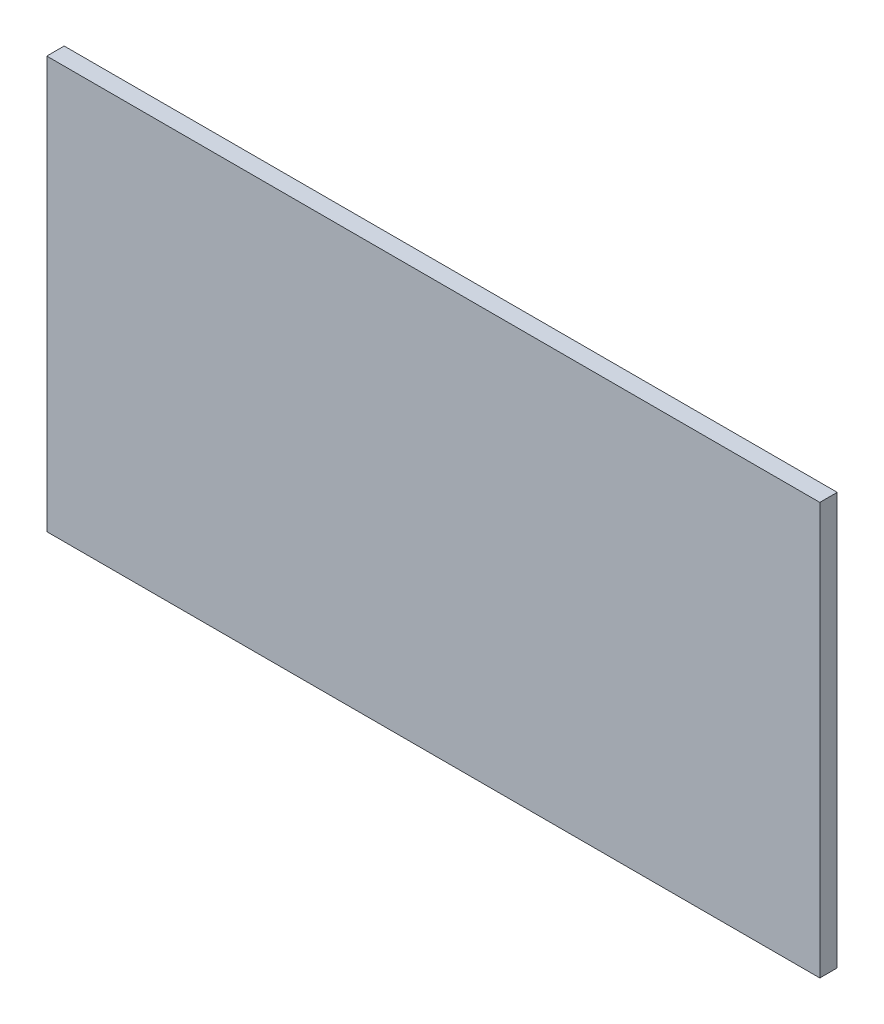
SolidWorks part; units mm, degrees
ref_plane "Alzado" through (0, 0, 0) normal (0, 0, 1) x (1, 0, 0)
ref_plane "Planta" through (0, 0, 0) normal (0, 1, 0) x (1, 0, 0)
ref_plane "Vista lateral" through (0, 0, 0) normal (1, 0, 0) x (0, 0, -1)
sketch "Croquis1" plane through (0, 0, 0) normal (0, 0, 1) x (1, 0, 0)
  line L1 (-57.8963, 16.3831) -> (-13.5012, 16.3831)
  line L2 (-57.8963, 16.3831) -> (-57.8963, -7.2712)
  line L3 (-57.8963, -7.2712) -> (-13.5012, -7.2712)
  line L4 (-13.5012, 16.3831) -> (-13.5012, -7.2712)
extrude "Saliente-Extruir1" add sketch "Croquis1" along normal blind 1
